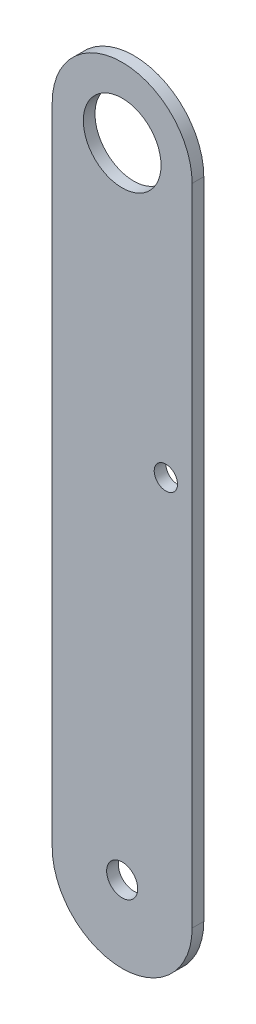
SolidWorks part; units mm, degrees
ref_plane "Front Plane" through (0, 0, 0) normal (0, 0, 1) x (1, 0, 0)
ref_plane "Top Plane" through (0, 0, 0) normal (0, 1, 0) x (1, 0, 0)
ref_plane "Right Plane" through (0, 0, 0) normal (1, 0, 0) x (0, 0, -1)
sketch "Sketch1" plane through (0, 0, 0) normal (0, 0, 1) x (1, 0, 0)
  line L0 (-15.5426, 34.4681) -> (-15.5426, -48.5106)
  line L1 (2.4574, 34.4681) -> (2.4574, -48.5106)
  arc A0 (-15.5426, 34.4681) -> (2.4574, 34.4681) centre (-6.5426, 34.4681) cw
  arc A2 (-15.5426, -48.5106) -> (2.4574, -48.5106) centre (-6.5426, -48.5106) ccw
  dimension "D1" = 18
extrude "Boss-Extrude1" add sketch "Sketch1" along normal blind 1.5
sketch "Sketch2" plane through (0, 0, 1.5) normal (0, 0, 1) x (1, 0, 0)
  line L0 (-6.5426, 29.4681) -> (-6.5426, 0) construction
  circle A0 centre (-6.5426, 34.4681) radius 5
  circle A1 centre (-0.92, 0) radius 1.5
  circle A2 centre (-6.5426, -47.642) radius 2
  point P9 (0, 0)
  dimension "D1" = 10
  dimension "D2" = 3
  dimension "D3" = 4
extrude "Cut-Extrude1" cut sketch "Sketch2" against normal blind 1.5
